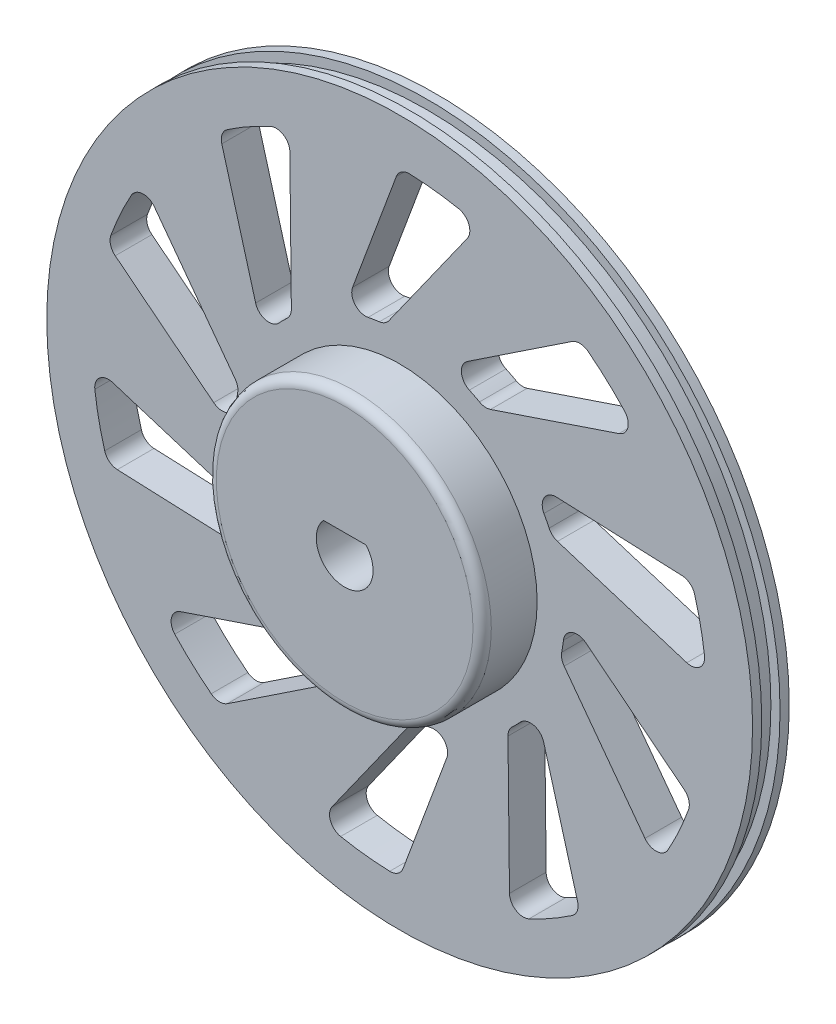
SolidWorks part; units mm, degrees
ref_plane "Спереди" through (0, 0, 0) normal (0, 0, 1) x (1, 0, 0)
ref_plane "Сверху" through (0, 0, 0) normal (0, 1, 0) x (1, 0, 0)
ref_plane "Справа" through (0, 0, 0) normal (1, 0, 0) x (0, 0, -1)
sketch "Эскиз1" plane through (0, 0, 0) normal (0, 0, 1) x (1, 0, 0)
  circle A0 centre (0, 0) radius 37.5
  dimension "D1" = 75
extrude "Бобышка-Вытянуть2" add sketch "Эскиз1" along normal blind 2
sketch "Эскиз2" plane through (0, 0, 2) normal (0, 0, 1) x (1, 0, 0)
  circle A0 centre (0, 0) radius 38.5
  circle A1 centre (0, 0) radius 37.5 construction
  dimension "D1" = 1
extrude "Бобышка-Вытянуть3" add sketch "Эскиз2" along normal blind 1
sketch "Эскиз3" plane through (0, 0, 0) normal (0, 0, -1) x (-1, 0, 0)
  circle A0 centre (0, 0) radius 38.5
  circle A1 centre (0, 0) radius 38.5 construction
extrude "Бобышка-Вытянуть4" add sketch "Эскиз3" along normal blind 1
sketch "Эскиз4" plane through (0, 0, -1) normal (0, 0, -1) x (-1, 0, 0)
  line L0 (2.3254, 2.05) -> (-2.3254, 2.05)
  line L1 (0, -3.1) -> (-5.9785, -3.1) construction
  arc A0 (-2.3254, 2.05) -> (2.3254, 2.05) centre (0, 0) ccw
  dimension "D1" = 6.2
  dimension "D2" = 5.15
sketch "Эскиз6" plane through (0, 0, 3) normal (0, 0, 1) x (1, 0, 0)
  circle A0 centre (0, 0) radius 15
  dimension "D1" = 30
extrude "Бобышка-Вытянуть6" add sketch "Эскиз6" along normal blind 6
extrude "Вырез-Вытянуть4" cut sketch "Эскиз4" against normal through all
sketch "Эскиз7" plane through (0, 0, 3) normal (0, 0, 1) x (1, 0, 0)
  line L0 (0, 0) -> (0, 33.5) construction
  line L1 (0, 0) -> (-11.4577, 31.4797) construction
  line L2 (-1.177, 18.4836) -> (7.3761, 30.5347)
  line L3 (7.3761, 30.5347) -> (8.6704, 32.3585) construction
  line L4 (-5.1366, 19.6619) -> (-0.3693, 32.5052)
  line L5 (-0.3693, 32.5052) -> (0, 33.5) construction
  line L6 (7.4014, 18.926) -> (18.8073, 26.5143)
  line L7 (9.9121, 15.6453) -> (23.9152, 20.3676)
  line L8 (17.1123, 10.961) -> (30.8002, 10.3958)
  line L9 (17.2152, 6.8311) -> (31.3196, 2.4207)
  line L10 (20.2868, -1.1907) -> (31.0284, -9.6935)
  line L11 (17.9426, -4.5923) -> (26.7609, -16.4508)
  line L12 (15.7125, -12.8876) -> (19.4048, -26.0802)
  line L13 (11.8166, -14.2617) -> (11.9805, -29.0387)
  line L14 (5.1366, -19.6619) -> (0.3693, -32.5052)
  line L15 (1.177, -18.4836) -> (-7.3761, -30.5347)
  line L16 (-7.4014, -18.926) -> (-18.8073, -26.5143)
  line L17 (-9.9121, -15.6453) -> (-23.9152, -20.3676)
  line L18 (-17.1123, -10.961) -> (-30.8002, -10.3958)
  line L19 (-17.2152, -6.8311) -> (-31.3196, -2.4207)
  line L20 (-20.2868, 1.1907) -> (-31.0284, 9.6935)
  line L21 (-17.9426, 4.5923) -> (-26.7609, 16.4508)
  line L22 (-15.7125, 12.8876) -> (-19.4048, 26.0802)
  line L23 (-11.8166, 14.2617) -> (-11.9805, 29.0387)
  circle A0 centre (0, 0) radius 18 construction
  circle A1 centre (0, 0) radius 33.5 construction
  circle A2 centre (0, 0) radius 38.5 construction
  circle A3 centre (0, 0) radius 15 construction
  arc A4 (1.0856, 33.4824) -> (6.4412, 32.8749) centre (0, 0) cw
  arc A5 (-3.4434, 17.6676) -> (-2.2156, 17.8631) centre (0, 0) cw
  arc A6 (-3.4434, 17.6676) -> (-5.1366, 19.6619) centre (-3.7303, 19.1399) cw
  arc A7 (6.4412, 32.8749) -> (7.3761, 30.5347) centre (6.1528, 31.4029) cw
  arc A8 (-2.2156, 17.8631) -> (-1.177, 18.4836) centre (-2.4002, 19.3517) ccw
  arc A9 (1.0856, 33.4824) -> (-0.3693, 32.5052) centre (1.037, 31.9832) ccw
  arc A10 (20.5587, 26.4497) -> (18.8073, 26.5143) centre (19.6382, 25.2654) ccw
  arc A11 (20.5587, 26.4497) -> (24.5345, 22.8103) centre (0, 0) cw
  arc A12 (24.5345, 22.8103) -> (23.9152, 20.3676) centre (23.4359, 21.7889) cw
  arc A13 (7.599, 16.3173) -> (8.7072, 15.7539) centre (0, 0) cw
  arc A14 (8.7072, 15.7539) -> (9.9121, 15.6453) centre (9.4328, 17.0667) ccw
  arc A15 (7.599, 16.3173) -> (7.4014, 18.926) centre (8.2322, 17.6771) cw
  arc A16 (32.1791, 9.3142) -> (30.8002, 10.3958) centre (30.7383, 8.8971) ccw
  arc A17 (32.1791, 9.3142) -> (33.2564, 4.0329) centre (0, 0) cw
  arc A18 (33.2564, 4.0329) -> (31.3196, 2.4207) centre (31.7673, 3.8523) cw
  arc A19 (15.7388, 8.7344) -> (16.3042, 7.6272) centre (0, 0) cw
  arc A20 (16.3042, 7.6272) -> (17.2152, 6.8311) centre (17.6629, 8.2628) ccw
  arc A21 (15.7388, 8.7344) -> (17.1123, 10.961) centre (17.0504, 9.4623) cw
  arc A22 (31.5082, -11.3791) -> (31.0284, -9.6935) centre (30.0974, -10.8696) ccw
  arc A23 (31.5082, -11.3791) -> (29.2755, -16.2849) centre (0, 0) cw
  arc A24 (29.2755, -16.2849) -> (26.7609, -16.4508) centre (27.9646, -15.5557) cw
  arc A25 (17.8669, -2.1847) -> (17.6735, -3.4128) centre (0, 0) cw
  arc A26 (17.6735, -3.4128) -> (17.9426, -4.5923) centre (19.1463, -3.6973) ccw
  arc A27 (17.8669, -2.1847) -> (20.2868, -1.1907) centre (19.3558, -2.3668) cw
  arc A28 (18.8022, -27.7259) -> (19.4048, -26.0802) centre (17.9603, -26.4845) ccw
  arc A29 (18.8022, -27.7259) -> (14.1123, -30.3824) centre (0, 0) cw
  arc A30 (14.1123, -30.3824) -> (11.9805, -29.0387) centre (13.4804, -29.022) cw
  arc A31 (13.1705, -12.2694) -> (12.2921, -13.1493) centre (0, 0) cw
  arc A32 (12.2921, -13.1493) -> (11.8166, -14.2617) centre (13.3165, -14.245) ccw
  arc A33 (13.1705, -12.2694) -> (15.7125, -12.8876) centre (14.268, -13.2919) cw
  arc A34 (-1.0856, -33.4824) -> (0.3693, -32.5052) centre (-1.037, -31.9832) ccw
  arc A35 (-1.0856, -33.4824) -> (-6.4412, -32.8749) centre (0, 0) cw
  arc A36 (-6.4412, -32.8749) -> (-7.3761, -30.5347) centre (-6.1528, -31.4029) cw
  arc A37 (3.4434, -17.6676) -> (2.2156, -17.8631) centre (0, 0) cw
  arc A38 (2.2156, -17.8631) -> (1.177, -18.4836) centre (2.4002, -19.3517) ccw
  arc A39 (3.4434, -17.6676) -> (5.1366, -19.6619) centre (3.7303, -19.1399) cw
  arc A40 (-20.5587, -26.4497) -> (-18.8073, -26.5143) centre (-19.6382, -25.2654) ccw
  arc A41 (-20.5587, -26.4497) -> (-24.5345, -22.8103) centre (0, 0) cw
  arc A42 (-24.5345, -22.8103) -> (-23.9152, -20.3676) centre (-23.4359, -21.7889) cw
  arc A43 (-7.599, -16.3173) -> (-8.7072, -15.7539) centre (0, 0) cw
  arc A44 (-8.7072, -15.7539) -> (-9.9121, -15.6453) centre (-9.4328, -17.0667) ccw
  arc A45 (-7.599, -16.3173) -> (-7.4014, -18.926) centre (-8.2322, -17.6771) cw
  arc A46 (-32.1791, -9.3142) -> (-30.8002, -10.3958) centre (-30.7383, -8.8971) ccw
  arc A47 (-32.1791, -9.3142) -> (-33.2564, -4.0329) centre (0, 0) cw
  arc A48 (-33.2564, -4.0329) -> (-31.3196, -2.4207) centre (-31.7673, -3.8523) cw
  arc A49 (-15.7388, -8.7344) -> (-16.3042, -7.6272) centre (0, 0) cw
  arc A50 (-16.3042, -7.6272) -> (-17.2152, -6.8311) centre (-17.6629, -8.2628) ccw
  arc A51 (-15.7388, -8.7344) -> (-17.1123, -10.961) centre (-17.0504, -9.4623) cw
  arc A52 (-31.5082, 11.3791) -> (-31.0284, 9.6935) centre (-30.0974, 10.8696) ccw
  arc A53 (-31.5082, 11.3791) -> (-29.2755, 16.2849) centre (0, 0) cw
  arc A54 (-29.2755, 16.2849) -> (-26.7609, 16.4508) centre (-27.9646, 15.5557) cw
  arc A55 (-17.8669, 2.1847) -> (-17.6735, 3.4128) centre (0, 0) cw
  arc A56 (-17.6735, 3.4128) -> (-17.9426, 4.5923) centre (-19.1463, 3.6973) ccw
  arc A57 (-17.8669, 2.1847) -> (-20.2868, 1.1907) centre (-19.3558, 2.3668) cw
  arc A58 (-18.8022, 27.7259) -> (-19.4048, 26.0802) centre (-17.9603, 26.4845) ccw
  arc A59 (-18.8022, 27.7259) -> (-14.1123, 30.3824) centre (0, 0) cw
  arc A60 (-14.1123, 30.3824) -> (-11.9805, 29.0387) centre (-13.4804, 29.022) cw
  arc A61 (-13.1705, 12.2694) -> (-12.2921, 13.1493) centre (0, 0) cw
  arc A62 (-12.2921, 13.1493) -> (-11.8166, 14.2617) centre (-13.3165, 14.245) ccw
  arc A63 (-13.1705, 12.2694) -> (-15.7125, 12.8876) centre (-14.268, 13.2919) cw
  point P16 (-6.1564, 16.9145)
  point P22 (-1.5688, 17.9315)
  point P136 (0, 0)
  dimension "D1" = 5
  dimension "D2" = 3
  dimension "D5" = 1.5
  dimension "D3" = 15
  dimension "D4" = 15
  dimension "D6" = 20
  dimension "D7" = 10
extrude "Вырез-Вытянуть5" cut sketch "Эскиз7" against normal through all
fillet "Скругление1" radius 1 1 edges at (15, 0, 9)
